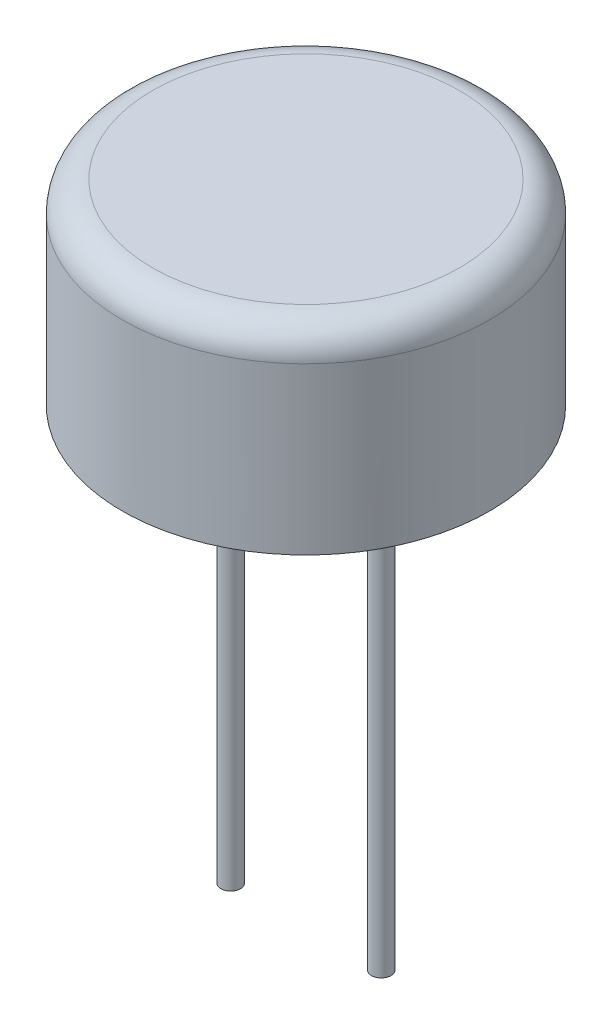
SolidWorks part; units mm, degrees
ref_plane "Front Plane" through (0, 0, 0) normal (0, 0, 1) x (1, 0, 0)
ref_plane "Top Plane" through (0, 0, 0) normal (0, 1, 0) x (1, 0, 0)
ref_plane "Right Plane" through (0, 0, 0) normal (1, 0, 0) x (0, 0, -1)
sketch "Sketch2" plane through (0, 0, 0) normal (0, 1, 0) x (1, 0, 0)
  circle A0 centre (0, 0) radius 6.1
  dimension "D1" = 12.2
extrude "Boss-Extrude1" add sketch "Sketch2" along normal blind 6.5
sketch "Sketch3" plane through (0, 0, 0) normal (0, -1, 0) x (1, 0, 0)
  circle A0 centre (-2.5, 0) radius 0.325
  circle A1 centre (2.5, 0) radius 0.325
  dimension "D1" = 5
  dimension "D3" = 0.65
  dimension "D4" = 0.65
  dimension "D2" = 2.5
extrude "Boss-Extrude2" add sketch "Sketch3" along normal blind 15
fillet "Fillet1" radius 1 1 edges at (0, 6.5, 6.1)
